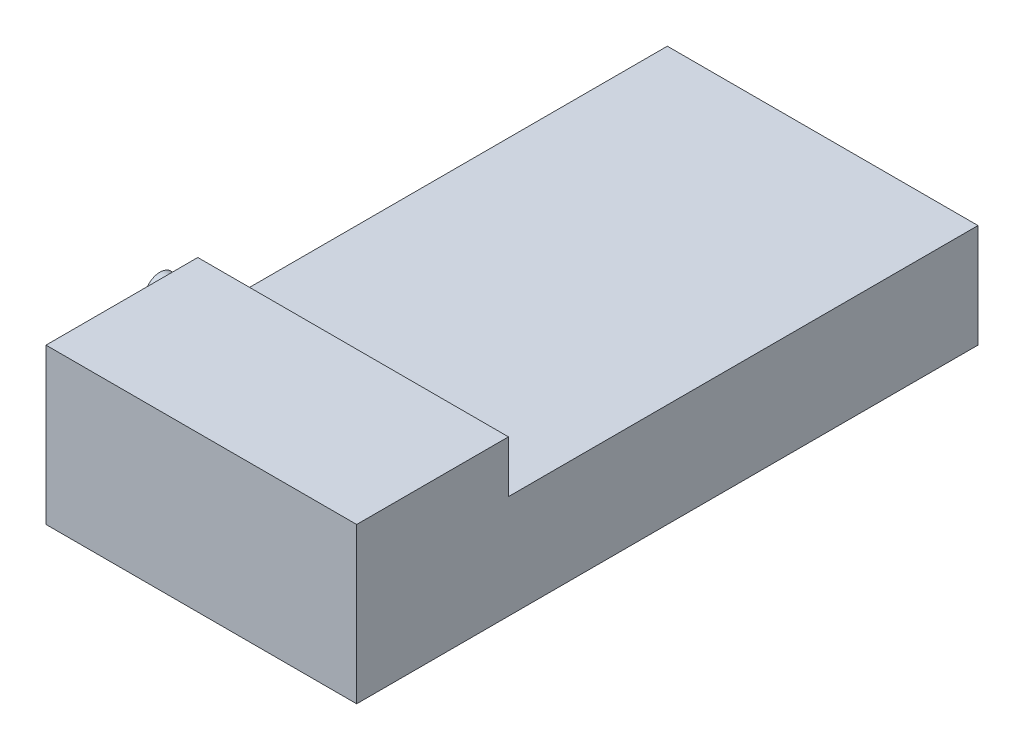
SolidWorks part; units mm, degrees
ref_plane "Front Plane" through (0, 0, 0) normal (0, 0, 1) x (1, 0, 0)
ref_plane "Top Plane" through (0, 0, 0) normal (0, 1, 0) x (1, 0, 0)
ref_plane "Right Plane" through (0, 0, 0) normal (1, 0, 0) x (0, 0, -1)
sketch "Sketch2" plane through (0, 0, 0) normal (0, 1, 0) x (1, 0, 0)
  line L1 (0, 0) -> (38.1, 0)
  line L2 (0, 0) -> (0, 76.2)
  line L3 (0, 76.2) -> (38.1, 76.2)
  line L4 (38.1, 0) -> (38.1, 76.2)
  dimension "D1" = 76.2
  dimension "D2" = 38.1
extrude "Boss-Extrude1" add sketch "Sketch2" along normal blind 12.7
sketch "Sketch3" plane through (0, 0, 0) normal (-1, 0, 0) x (0, 0, 1)
  line L0 (0, 12.7) -> (0, 0) construction
  circle A0 centre (-25.4, 6.4786) radius 1.905
  dimension "D1" = 3.81
  dimension "D2" = 25.4
extrude "Boss-Extrude3" add sketch "Sketch3" along normal blind 11.43 contours A0
sketch "Sketch4" plane through (38.1, 0, 0) normal (1, 0, 0) x (0, 0, -1)
  line L0 (0, 12.7) -> (76.2, 12.7) construction
  line L1 (0, 12.7) -> (0, 0) construction
  circle A0 centre (25.4, 6.35) radius 1.905
  dimension "D1" = 3.81
  dimension "D3" = 25.4
  dimension "D2" = 6.35
sketch "Sketch5" plane through (0, 12.7, 0) normal (0, 1, 0) x (1, 0, 0)
  line L0 (38.1, 0) -> (38.1, 76.2) construction
  line L1 (38.1, 18.6147) -> (0, 18.6147)
  line L2 (38.1, 18.6147) -> (38.1, 0)
  line L3 (38.1, 0) -> (0, 0)
  line L4 (0, 18.6147) -> (0, 0)
extrude "Boss-Extrude5" add sketch "Sketch5" along normal blind 2.54
sketch "Sketch6" plane through (0, 15.24, 0) normal (0, 1, 0) x (1, 0, 0)
  line L1 (38.1, 18.6147) -> (0, 18.6147)
  line L2 (38.1, 18.6147) -> (38.1, 0)
  line L3 (38.1, 0) -> (0, 0)
  line L4 (0, 18.6147) -> (0, 0)
extrude "Boss-Extrude6" add sketch "Sketch6" along normal blind 3.81
